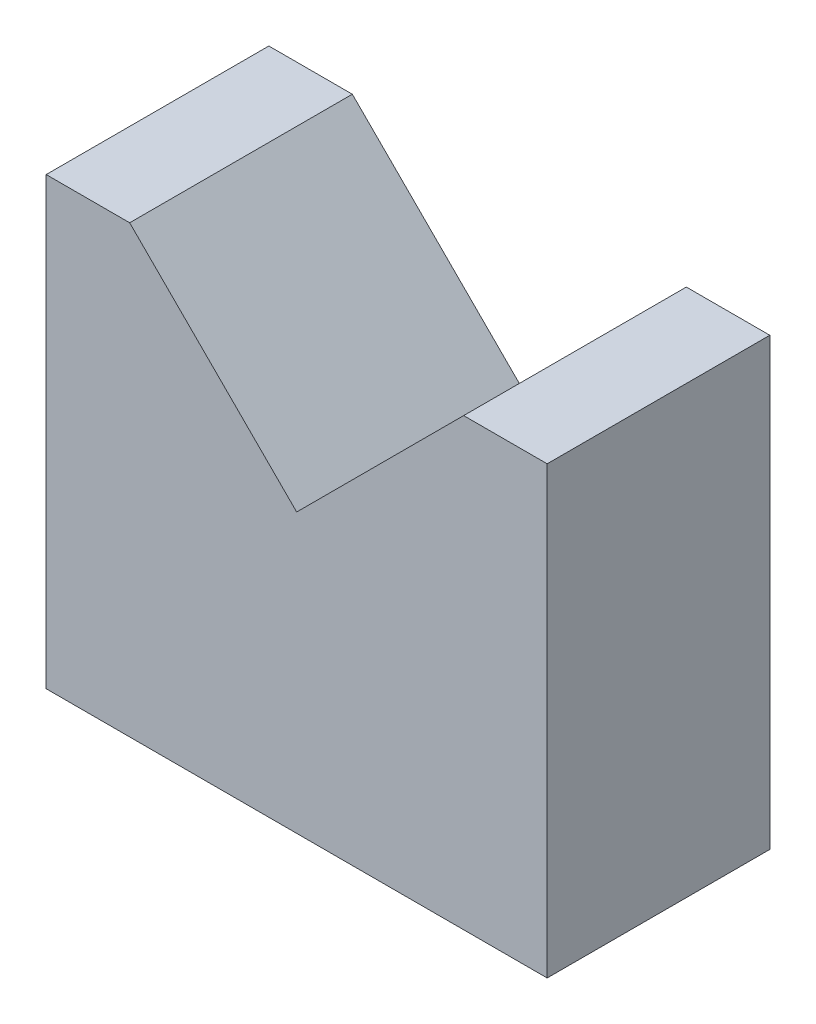
SolidWorks part; units mm, degrees
ref_plane "Front" through (0, 0, 0) normal (0, 0, 1) x (1, 0, 0)
ref_plane "Top" through (0, 0, 0) normal (0, 1, 0) x (1, 0, 0)
ref_plane "Right" through (0, 0, 0) normal (1, 0, 0) x (0, 0, -1)
sketch "Sketch1" plane through (0, 0, 0) normal (0, 0, 1) x (1, 0, 0)
  line L0 (-28.575, 50.8) -> (-19.05, 50.8)
  line L1 (-19.05, 50.8) -> (0, 31.75)
  line L2 (0, -50) -> (0, 50) construction
  line L3 (0, 31.75) -> (19.05, 50.8)
  line L4 (19.05, 50.8) -> (28.575, 50.8)
  line L5 (28.575, 50.8) -> (28.575, 0)
  line L6 (28.575, 0) -> (-28.575, 0)
  line L7 (-28.575, 0) -> (-28.575, 50.8)
  line L8 (50, 0) -> (-50, 0) construction
  point P2 (0, 0)
  point P12 (0, 30.9389)
  dimension "D1" = 57.15
  dimension "D2" = 50.8
  dimension "D3" = 90
  dimension "D4" = 31.75
extrude "Boss-Extrude1" add sketch "Sketch1" along normal mid plane 25.4 contours L0 L1 L3 L4 L5 L6 L7
